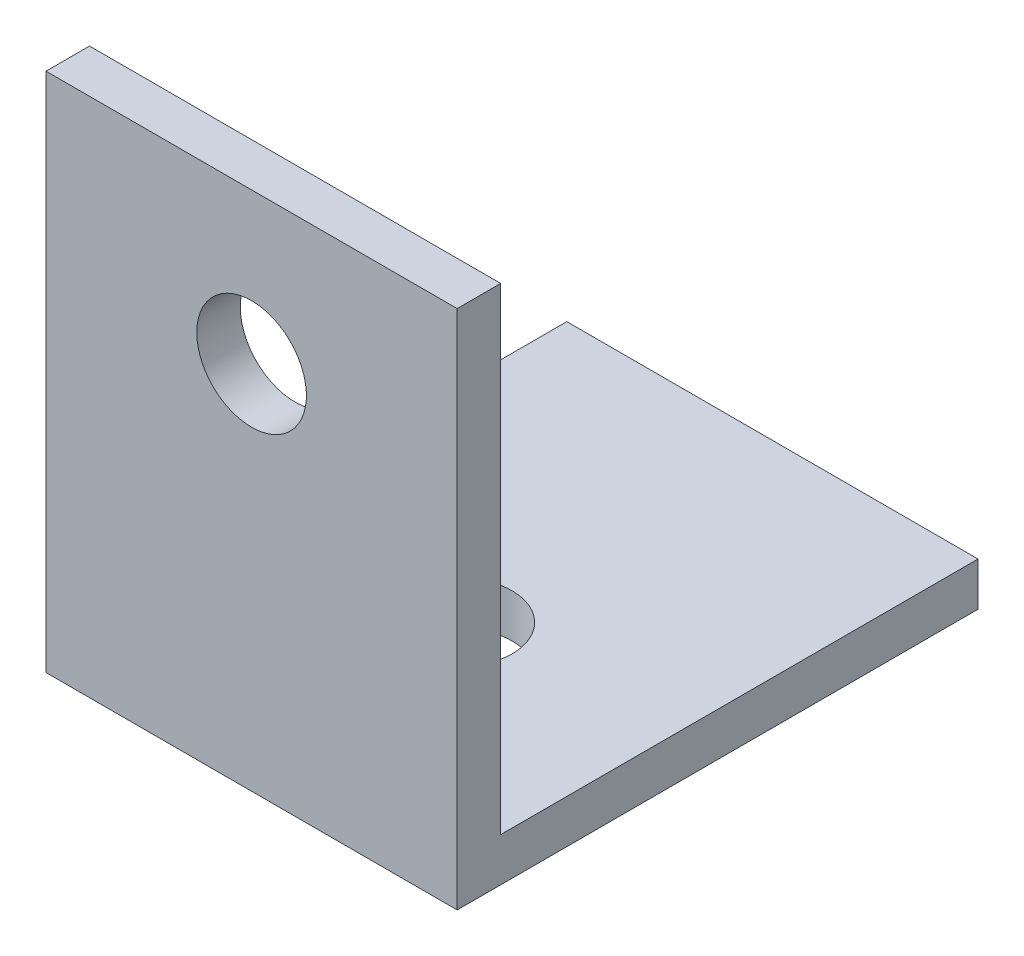
SolidWorks part; units mm, degrees
ref_plane "Front Plane" through (0, 0, 0) normal (0, 0, 1) x (1, 0, 0)
ref_plane "Top Plane" through (0, 0, 0) normal (0, 1, 0) x (1, 0, 0)
ref_plane "Right Plane" through (0, 0, 0) normal (1, 0, 0) x (0, 0, -1)
sketch "Sketch1" plane through (0, 0, 0) normal (0, 0, 1) x (1, 0, 0)
  line L1 (0, 0) -> (30, 0)
  line L2 (0, 0) -> (0, 38)
  line L3 (0, 38) -> (30, 38)
  line L4 (30, 0) -> (30, 38)
  dimension "D1" = 30
  dimension "D2" = 38
extrude "Boss-Extrude1" add sketch "Sketch1" along normal blind 3.175
sketch "Sketch2" plane through (0, 0, 0) normal (0, 0, -1) x (-1, 0, 0)
  line L0 (0, 38) -> (0, 0) construction
  line L1 (-30, 0) -> (0, 0)
  line L2 (-30, 0) -> (-30, 3.175)
  line L3 (-30, 3.175) -> (0, 3.175)
  line L4 (0, 0) -> (0, 3.175)
  dimension "D1" = 3.175
extrude "Boss-Extrude2" add sketch "Sketch2" along normal blind 34.825
sketch "Sketch3" plane through (0, 0, 0) normal (0, 0, -1) x (-1, 0, 0)
  line L1 (-30, 3.175) -> (-30, 38) construction
  line L2 (-30, 0) -> (0, 0) construction
  circle A0 centre (-15, 27) radius 4
  dimension "D1" = 8
  dimension "D2" = 27
  dimension "D3" = 15
extrude "Cut-Extrude1" cut sketch "Sketch3" against normal through all
sketch "Sketch4" plane through (0, 3.175, 0) normal (0, 1, 0) x (1, 0, 0)
  line L1 (30, 34.825) -> (30, 0) construction
  line L2 (0, -3.175) -> (30, -3.175) construction
  circle A0 centre (15, 11.825) radius 4
  dimension "D1" = 8
  dimension "D2" = 15
  dimension "D3" = 15
extrude "Cut-Extrude2" cut sketch "Sketch4" against normal through all
